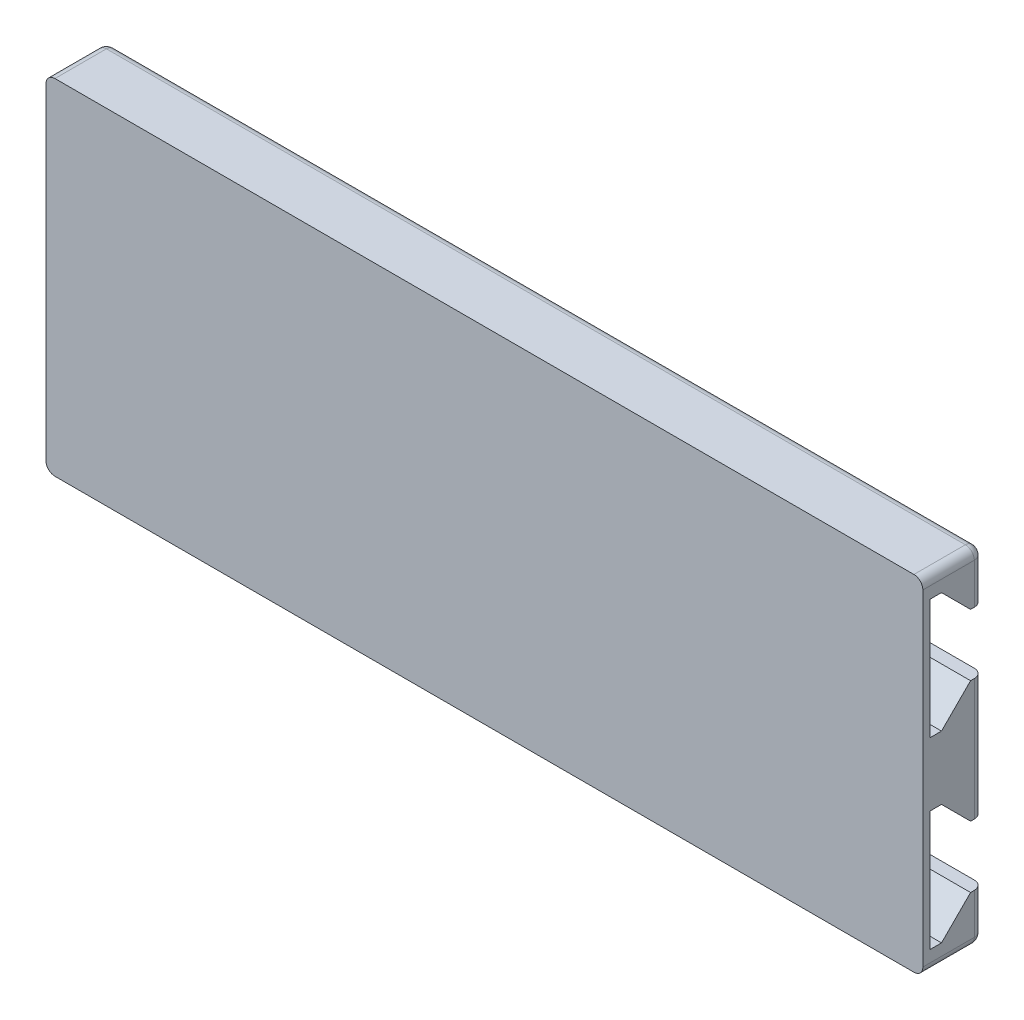
SolidWorks part; units mm, degrees
ref_plane "Front Plane" through (0, 0, 0) normal (1, 0, 0) x (0, 1, 0)
ref_plane "Top Plane" through (0, 0, 0) normal (0, 0, 1) x (0, 1, 0)
ref_plane "Right Plane" through (0, 0, 0) normal (0, 1, 0) x (-1, 0, 0)
sketch "Sketch1" plane through (0, 0, 0) normal (0, 0, 1) x (0, 1, 0)
  line L1 (-38.5, -98) -> (38.5, -98)
  line L2 (-38.5, -98) -> (-38.5, 98)
  line L3 (-38.5, 98) -> (38.5, 98)
  line L4 (38.5, -98) -> (38.5, 98)
  line L5 (-38.5, -98) -> (38.5, 98) construction
  line L6 (-38.5, 98) -> (38.5, -98) construction
  point P0 (0, 0)
  dimension "D1" = 77
  dimension "D2" = 196
extrude "Boss-Extrude1" add sketch "Sketch1" along normal blind 13.5
sketch "Sketch2" plane through (-98, 0, 0) normal (-1, 0, 0) x (0, -1, 0)
  line L0 (0, 0) -> (0, 13.5) construction
  line L1 (7.5, 11.5) -> (7.5, 9.5) construction
  line L2 (7.5, 9.5) -> (14, 3) construction
  line L3 (14, 3) -> (14, 0) construction
  line L4 (-38.5, 0) -> (38.5, 0)
  line L5 (38.5, 0) -> (38.5, 13.5)
  line L6 (38.5, 13.5) -> (-38.5, 13.5)
  line L7 (-38.5, 13.5) -> (-38.5, 0)
  line L8 (-38.5, 0) -> (38.5, 0)
  line L9 (38.5, 0) -> (38.5, 13.5)
  line L10 (38.5, 13.5) -> (-38.5, 13.5)
  line L11 (-38.5, 13.5) -> (-38.5, 0)
  line L12 (33.5, 11.5) -> (33.5, 9.5) construction
  line L13 (33.5, 9.5) -> (27, 3) construction
  line L14 (27, 3) -> (27, 0) construction
  line L15 (7.5, 11.5) -> (33.5, 11.5) construction
  line L16 (27.4, 2.8343) -> (27.4, 0)
  line L17 (33.9, 9.3343) -> (27.4, 2.8343)
  line L18 (33.9, 11.9) -> (33.9, 9.3343)
  line L19 (7.1, 11.9) -> (33.9, 11.9)
  line L20 (7.1, 11.9) -> (7.1, 9.3343)
  line L21 (7.1, 9.3343) -> (13.6, 2.8343)
  line L22 (13.6, 2.8343) -> (13.6, 0)
  line L23 (-13.6, 2.8343) -> (-13.6, 0)
  line L24 (-7.1, 9.3343) -> (-13.6, 2.8343)
  line L25 (-7.1, 11.9) -> (-7.1, 9.3343)
  line L26 (-7.1, 11.9) -> (-33.9, 11.9)
  line L27 (-33.9, 11.9) -> (-33.9, 9.3343)
  line L28 (-33.9, 9.3343) -> (-27.4, 2.8343)
  line L29 (-27.4, 2.8343) -> (-27.4, 0)
  dimension "D2" = 135
  dimension "D3" = 135
  dimension "D4" = 2
  dimension "D5" = 6.5
  dimension "D6" = 26
  dimension "D7" = 2
  dimension "D8" = 5
  dimension "D1" = 0
  dimension "D9" = 0.4
extrude "Cut-Extrude1" cut sketch "Sketch2" against normal through all contours L21 L22 L8 L16 L17 L18 L19 L20 | L28 L29 L8 L23 L24 L25 L26 L27
sketch "Sketch3" plane through (0, -38.5, 0) normal (0, -1, 0) x (1, 0, 0)
  line L0 (0, 13.5) -> (0, 0) construction
  line L1 (-98, 13.5) -> (98, 13.5) construction
  line L2 (-86.5, 11.5) -> (-60.5, 11.5) construction
  line L3 (-60.5, 11.5) -> (-60.5, 9.5) construction
  line L4 (-60.5, 9.5) -> (-67, 3) construction
  line L5 (-67, 3) -> (-67, 0) construction
  line L6 (-86.5, 11.5) -> (-86.5, 9.5) construction
  line L7 (-86.5, 9.5) -> (-80, 3) construction
  line L8 (-80, 3) -> (-80, 0) construction
  line L10 (-98, 0) -> (98, 0) construction
  line L11 (-98, 13.5) -> (-98, 16) construction
  line L12 (-98, 16) -> (0, 16) construction
  line L13 (0, 16) -> (0, 13.5) construction
  line L14 (-98, 0) -> (98, 0)
  line L15 (98, 0) -> (98, 13.5)
  line L16 (98, 13.5) -> (-98, 13.5)
  line L17 (-98, 13.5) -> (-98, 0)
  line L18 (-98, 0) -> (98, 0)
  line L19 (98, 0) -> (98, 13.5)
  line L20 (98, 13.5) -> (-98, 13.5)
  line L21 (-98, 13.5) -> (-98, 0)
  line L22 (-49, 16) -> (-49, 13.5) construction
  line L23 (-98, 16) -> (-86.5, 11.5) construction
  line L24 (-60.5, 11.5) -> (-49, 16) construction
  line L25 (-80.4, 2.8343) -> (-80.4, 0)
  line L26 (-86.9, 9.3343) -> (-80.4, 2.8343)
  line L27 (-86.9, 11.9) -> (-86.9, 9.3343)
  line L28 (-86.9, 11.9) -> (-60.1, 11.9)
  line L29 (-60.1, 11.9) -> (-60.1, 9.3343)
  line L30 (-60.1, 9.3343) -> (-66.6, 2.8343)
  line L31 (-66.6, 2.8343) -> (-66.6, 0)
  line L32 (-37.9, 11.9) -> (-37.9, 9.3343)
  line L33 (-37.9, 9.3343) -> (-31.4, 2.8343)
  line L34 (-31.4, 2.8343) -> (-31.4, 0)
  line L35 (-17.6, 2.8343) -> (-17.6, 0)
  line L36 (-11.1, 9.3343) -> (-17.6, 2.8343)
  line L37 (-11.1, 11.9) -> (-11.1, 9.3343)
  line L38 (-11.1, 11.9) -> (-37.9, 11.9)
  line L39 (80.4, 2.8343) -> (80.4, 0)
  line L40 (31.4, 2.8343) -> (31.4, 0)
  line L41 (17.6, 2.8343) -> (17.6, 0)
  line L42 (11.1, 9.3343) -> (17.6, 2.8343)
  line L43 (11.1, 11.9) -> (11.1, 9.3343)
  line L44 (11.1, 11.9) -> (37.9, 11.9)
  line L45 (37.9, 11.9) -> (37.9, 9.3343)
  line L46 (37.9, 9.3343) -> (31.4, 2.8343)
  line L47 (66.6, 2.8343) -> (66.6, 0)
  line L48 (60.1, 9.3343) -> (66.6, 2.8343)
  line L49 (60.1, 11.9) -> (60.1, 9.3343)
  line L50 (86.9, 11.9) -> (60.1, 11.9)
  line L51 (86.9, 11.9) -> (86.9, 9.3343)
  line L52 (86.9, 9.3343) -> (80.4, 2.8343)
  line M33 (-98, 0) -> (98, 0)
  dimension "D1" = 135
  dimension "D2" = 135
  dimension "D3" = 6.5
  dimension "D4" = 26
  dimension "D5" = 2
  dimension "D6" = 2
  dimension "D7" = 0.4
  dimension "D9" = 5
  dimension "D8" = 0
extrude "Cut-Extrude2" cut sketch "Sketch3" along normal up to surface (67.8 mm away) from surface contours L31 L30 L29 L28 L27 L26 L25 L18 | L37 L38 L32 L33 L34 L18 L35 L36 | L46 L45 L44 L43 L42 L41 L18 L40 | L52 L51 L50 L49 L48 L47 L39 M33
fillet "Fillet1" radius 2 12 edges at (0, 38.5, 0) (98, 38.5, 6.75) (98, 32.95, 0) (98, 0, 0) (98, -38.5, 6.75) (98, -32.95, 0) (0, -38.5, 0) (-98, 38.5, 6.75) (-98, 32.95, 0) (-98, 0, 0) (-98, -38.5, 6.75) (-98, -32.95, 0)
